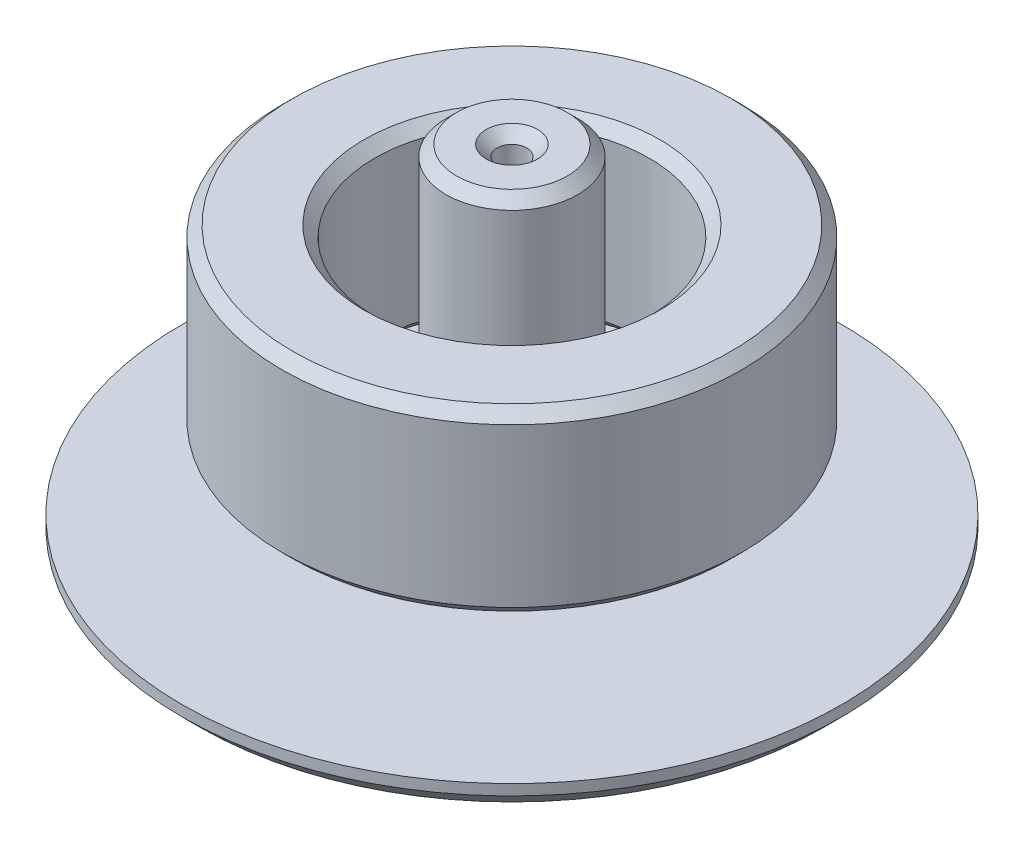
SolidWorks part; units mm, degrees
ref_plane "Front Plane" through (0, 0, 0) normal (0, 0, 1) x (1, 0, 0)
ref_plane "Top Plane" through (0, 0, 0) normal (0, 1, 0) x (1, 0, 0)
ref_plane "Right Plane" through (0, 0, 0) normal (1, 0, 0) x (0, 0, -1)
sketch "Sketch2" plane through (0, 0, 0) normal (1, 0, 0) x (0, 0, -1)
  line L0 (0, 44.5665) -> (0, -36.0862) construction
  line L1 (-32.25, 11.1) -> (-30.75, 12.6)
  line L2 (-30.75, 12.6) -> (-20.75, 12.6)
  line L3 (-32.25, 11.1) -> (-32.25, -11.1)
  line L4 (-30.75, -12.6) -> (-20.75, -12.6)
  line L5 (-19.25, 11.1) -> (-19.25, -11.1)
  line L6 (-32.25, 12.6) -> (-19.25, -12.6) construction
  line L7 (-32.25, -12.6) -> (-19.25, 12.6) construction
  line L8 (-20.75, 12.6) -> (-19.25, 11.1)
  line L9 (-32.25, -11.1) -> (-30.75, -12.6)
  line L10 (-20.75, -12.6) -> (-19.25, -11.1)
  line L11 (-42.25, 20.9) -> (-42.25, -20.1) construction
  line L12 (-39.75, -22.6) -> (-11.75, -22.6)
  line L13 (-9.25, 20.9) -> (-9.25, -20.1)
  line L14 (-43.75, 22.4) -> (-44.75, 22.4) construction
  line L15 (-46.25, -22.6) -> (-46.25, -24.1)
  line L16 (-43.75, -26.6) -> (-4.6, -26.6)
  line L17 (-2.1, -24.1) -> (-2.1, 20.9)
  line L18 (-3.6, 22.4) -> (-7.75, 22.4)
  line L19 (-46.25, -24.1) -> (-43.75, -26.6)
  line L20 (-4.6, -26.6) -> (-2.1, -24.1)
  line L21 (-42.25, -20.1) -> (-39.75, -22.6) construction
  line L22 (-11.75, -22.6) -> (-9.25, -20.1)
  line L23 (-42.25, 20.9) -> (-43.75, 22.4) construction
  line L24 (-44.75, 22.4) -> (-46.25, 20.9) construction
  line L25 (-7.75, 22.4) -> (-9.25, 20.9)
  line L26 (-2.1, 20.9) -> (-3.6, 22.4)
  line L27 (-39.75, -22.6) -> (-46.25, -22.6)
  line L28 (-46.25, 20.9) -> (-46.25, -22.6) construction
  point P3 (-25.75, 0)
  point P8 (-42.25, 22.4)
  point P17 (-42.25, -22.6)
  point P18 (-46.25, -26.6)
  point P19 (-9.25, 22.4)
  point P20 (-9.25, -22.6)
  point P21 (-2.1, -26.6)
  point P22 (-2.1, 22.4)
  point P25 (-46.25, 22.4)
  dimension "D1" = 38.5
  dimension "D2" = 64.5
  dimension "D3" = 25.2
  dimension "D4" = 10
  dimension "D5" = 10
  dimension "D6" = 10
  dimension "D11" = 45
  dimension "D12" = 4
  dimension "D13" = 4
  dimension "D14" = 4.2
revolve "Revolve1" add sketch "Sketch2" angle 360 about L0
